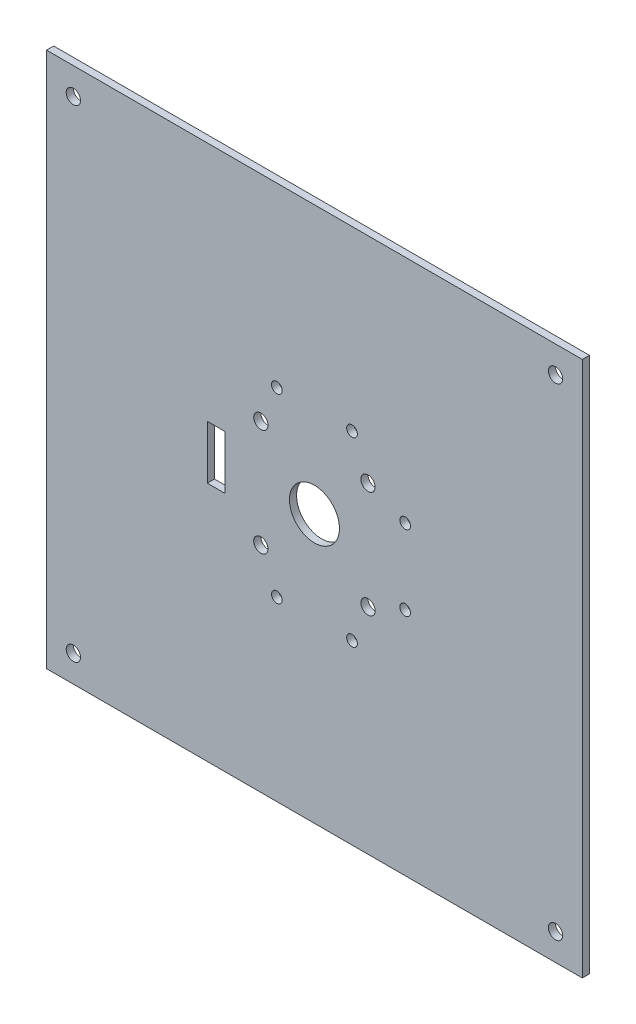
SolidWorks part; units mm, degrees
ref_plane "Alzado" through (0, 0, 0) normal (0, 0, 1) x (1, 0, 0)
ref_plane "Planta" through (0, 0, 0) normal (0, 1, 0) x (1, 0, 0)
ref_plane "Vista lateral" through (0, 0, 0) normal (1, 0, 0) x (0, 0, -1)
sketch "Croquis1" plane through (0, 0, 0) normal (0, 0, 1) x (1, 0, 0)
  line L1 (-75, -75) -> (75, -75)
  line L2 (-75, -75) -> (-75, 75)
  line L3 (-75, 75) -> (75, 75)
  line L4 (75, -75) -> (75, 75)
  line L5 (-75, -75) -> (75, 75) construction
  line L6 (-75, 75) -> (75, -75) construction
  point P0 (0, 0)
extrude "Saliente-Extruir1" add sketch "Croquis1" along normal blind 2
sketch "Croquis2" plane through (0, 0, 2) normal (0, 0, 1) x (1, 0, 0)
  line L1 (-67.5, -67.5) -> (67.5, -67.5)
  line L2 (-67.5, -67.5) -> (-67.5, 67.5)
  line L3 (-67.5, 67.5) -> (67.5, 67.5)
  line L4 (67.5, -67.5) -> (67.5, 67.5)
  line L5 (-67.5, -67.5) -> (67.5, 67.5) construction
  line L6 (-67.5, 67.5) -> (67.5, -67.5) construction
  line L7 (-15, -15) -> (15, -15)
  line L8 (-15, -15) -> (-15, 15)
  line L9 (-15, 15) -> (15, 15)
  line L10 (15, -15) -> (15, 15)
  line L11 (-15, -15) -> (15, 15) construction
  line L12 (-15, 15) -> (15, -15) construction
  line L13 (-30, -7.5) -> (-25, -7.5)
  line L14 (-30, -7.5) -> (-30, 7.5)
  line L15 (-30, 7.5) -> (-25, 7.5)
  line L16 (-25, -7.5) -> (-25, 7.5)
  line L17 (-30, -7.5) -> (-25, 7.5) construction
  line L18 (-30, 7.5) -> (-25, -7.5) construction
  circle A0 centre (-67.5, -67.5) radius 2
  circle A1 centre (67.5, -67.5) radius 2
  circle A2 centre (67.5, 67.5) radius 2
  circle A3 centre (-67.5, 67.5) radius 2
  circle A4 centre (0, 0) radius 7
  circle A5 centre (-15, -15) radius 2
  circle A6 centre (15, -15) radius 2
  circle A7 centre (15, 15) radius 2
  circle A8 centre (-15, 15) radius 2
  circle A9 centre (0, 0) radius 27.5
  circle A10 centre (-27.5, 0) radius 1.5
  circle A11 centre (-25.4067, 10.5238) radius 1.5
  circle A12 centre (-19.4454, 19.4454) radius 1.5
  circle A13 centre (-10.5238, 25.4067) radius 1.5
  circle A14 centre (0, 27.5) radius 1.5
  circle A15 centre (10.5238, 25.4067) radius 1.5
  circle A16 centre (19.4454, 19.4454) radius 1.5
  circle A17 centre (25.4067, 10.5238) radius 1.5
  circle A18 centre (27.5, 0) radius 1.5
  circle A19 centre (25.4067, -10.5238) radius 1.5
  circle A20 centre (19.4454, -19.4454) radius 1.5
  circle A21 centre (10.5238, -25.4067) radius 1.5
  circle A22 centre (0, -27.5) radius 1.5
  circle A23 centre (-10.5238, -25.4067) radius 1.5
  circle A24 centre (-19.4454, -19.4454) radius 1.5
  circle A25 centre (-25.4067, -10.5238) radius 1.5
  point P0 (0, 0)
  point P62 (0, 0)
  dimension "D1" = 2
  dimension "D4" = 2
  dimension "D6" = 16
  dimension "D2" = 2
  dimension "D3" = 135
  dimension "D5" = 2
extrude "Cortar-Extruir1" cut sketch "Croquis2" against normal blind 2 contours L16 L15 L14 L13 | A4 | A7 | A8 | A6 | A5 | A17 | A15 | A13 | A19 | A21 | A23 | A1 | A0 | A3 | A2
